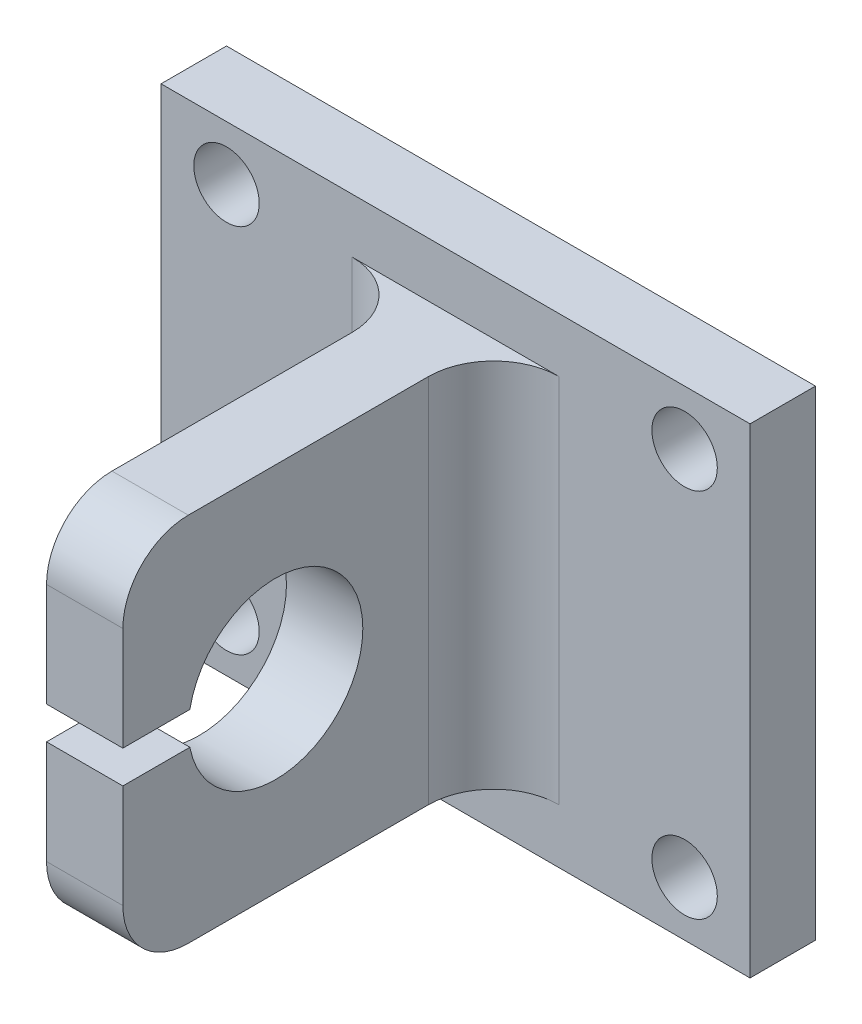
SolidWorks part; units mm, degrees
ref_plane "Front Plane" through (0, 0, 0) normal (0, 0, 1) x (1, 0, 0)
ref_plane "Top Plane" through (0, 0, 0) normal (0, 1, 0) x (1, 0, 0)
ref_plane "Right Plane" through (0, 0, 0) normal (1, 0, 0) x (0, 0, -1)
sketch "Sketch1" plane through (0, 0, 0) normal (0, 0, 1) x (1, 0, 0)
  line L1 (-13.5, -11) -> (13.5, -11)
  line L2 (-13.5, -11) -> (-13.5, 11)
  line L3 (-13.5, 11) -> (13.5, 11)
  line L4 (13.5, -11) -> (13.5, 11)
  line L5 (-13.5, -11) -> (13.5, 11) construction
  line L6 (-13.5, 11) -> (13.5, -11) construction
  line L7 (10.5, 8.5) -> (10.5, -8.5) construction
  line L8 (10.5, -8.5) -> (-10.5, -8.5) construction
  circle A2 centre (10.5, 8.5) radius 1.5
  circle A3 centre (10.5, -8.5) radius 1.5
  circle A4 centre (-10.5, -8.5) radius 1.5
  circle A5 centre (-10.5, 8.5) radius 1.5
  point P0 (0, 0)
  point P21 (0, -8.5)
  point P22 (0, -11)
  point P23 (10.5, 0)
  point P24 (13.5, 0)
  dimension "D5" = 3
  dimension "D1" = 27
  dimension "D2" = 22
  dimension "D6" = 17
  dimension "D7" = 21
extrude "Boss-Extrude1" add sketch "Sketch1" along normal blind 3
sketch "Sketch2" plane through (0, 0, 3) normal (0, 0, 1) x (1, 0, 0)
  line L1 (-1.75, 8.5) -> (1.75, 8.5)
  line L2 (-1.75, 8.5) -> (-1.75, -8.5)
  line L3 (-1.75, -8.5) -> (1.75, -8.5)
  line L4 (1.75, 8.5) -> (1.75, -8.5)
  line L5 (-13.5, -11) -> (13.5, -11) construction
  line L6 (1.75, 6.1093) -> (-1.75, 6.1093) construction
  line L7 (13.5, -11) -> (13.5, 11) construction
  point P4 (0, 0)
  point P10 (0, -11)
  point P11 (0, 6.1093)
  point P12 (0, 0)
  point P14 (13.5, 0)
  point P15 (1.75, 0)
  dimension "D1" = 3.5
  dimension "D2" = 17
extrude "Boss-Extrude2" add sketch "Sketch2" along normal blind 17
sketch "Sketch3" plane through (1.75, 0, 0) normal (1, 0, 0) x (0, 0, -1)
  line L0 (-20, -8.5) -> (-20, 8.5) construction
  line L1 (-3, -8.5) -> (-3, 8.5) construction
  circle A0 centre (-13, 0) radius 4
  point P5 (-20, 0)
  dimension "D1" = 8
  dimension "D2" = 10
extrude "Cut-Extrude1" cut sketch "Sketch3" against normal through all both and the other way through all
sketch "Sketch4" plane through (1.75, 0, 0) normal (1, 0, 0) x (0, 0, -1)
  line L1 (-22.3796, -0.75) -> (-14.282, -0.75)
  line L2 (-22.3796, -0.75) -> (-22.3796, 0.75)
  line L3 (-22.3796, 0.75) -> (-14.282, 0.75)
  line L4 (-14.282, -0.75) -> (-14.282, 0.75)
  line L5 (-20, -8.5) -> (-20, 8.5) construction
  point P6 (-20, 0)
  point P7 (-22.3796, 0)
  dimension "D1" = 1.5
extrude "Cut-Extrude2" cut sketch "Sketch4" against normal through all both and the other way through all
fillet "Fillet1" radius 3 2 edges at (-1.75, 0, 3) (1.75, 0, 3)
fillet "Fillet2" radius 3 2 edges at (0, 8.5, 20) (0, -8.5, 20)
